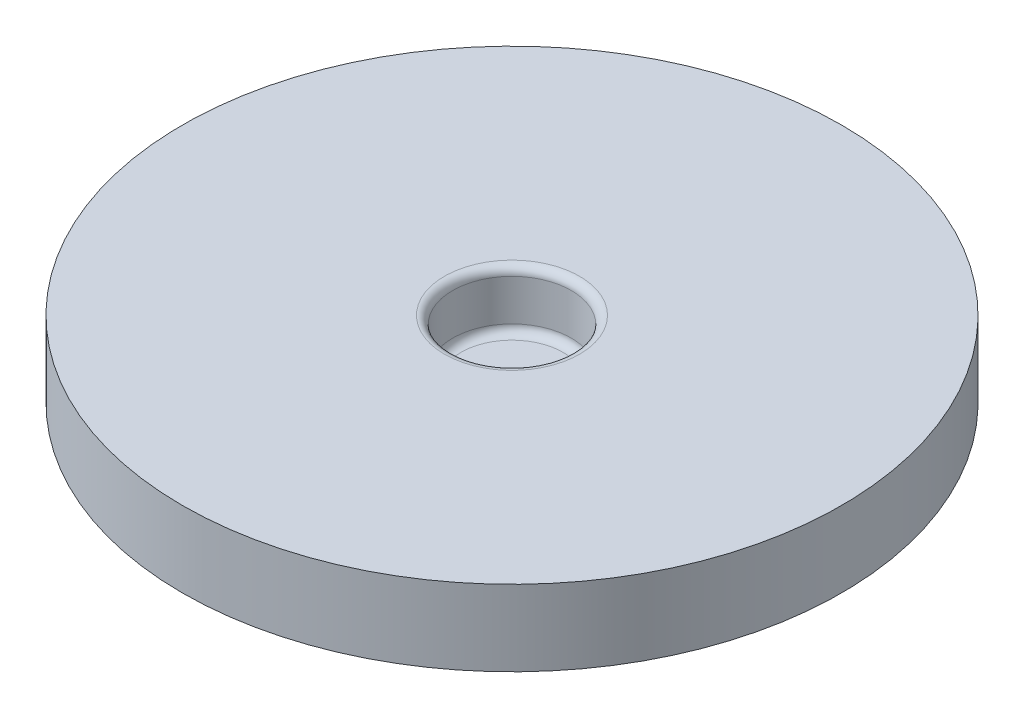
SolidWorks part; units mm, degrees
ref_plane "前视基准面" through (0, 0, 0) normal (0, 0, 1) x (1, 0, 0)
ref_plane "上视基准面" through (0, 0, 0) normal (0, 1, 0) x (1, 0, 0)
ref_plane "右视基准面" through (0, 0, 0) normal (1, 0, 0) x (0, 0, -1)
sketch "草图1" plane through (0, 0, 0) normal (0, 1, 0) x (1, 0, 0)
  circle A0 centre (0, 0) radius 20
  dimension "D1" = 40
extrude "凸台-拉伸1" add sketch "草图1" along normal blind 4.6
sketch "草图2" plane through (0, 4.6, 0) normal (0, 1, 0) x (1, 0, 0)
  circle A0 centre (0, 0) radius 3.6
  dimension "D1" = 7.2
extrude "切除-拉伸1" cut sketch "草图2" against normal blind 3.5
fillet "圆角1" radius 0.5 2 edges at (0, 4.6, 3.6) (0, 1.1, 3.6)
